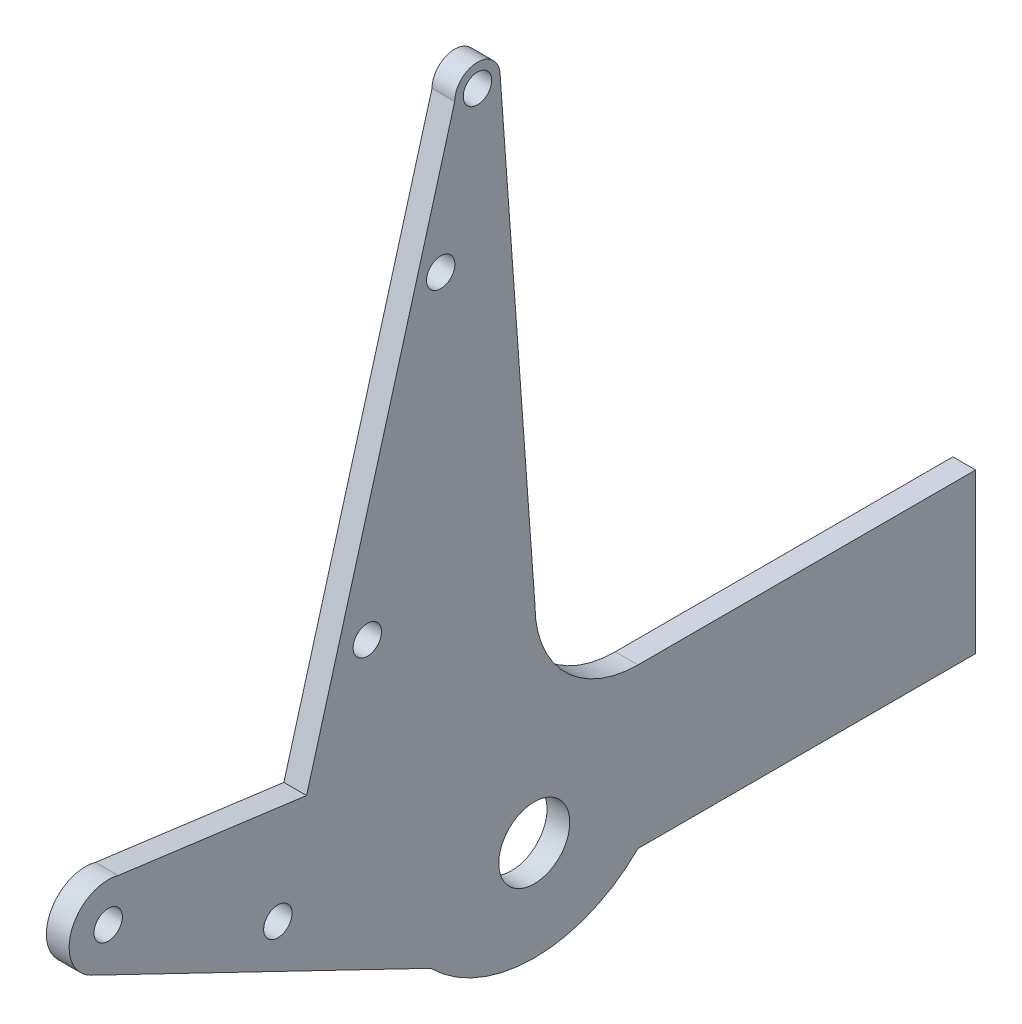
SolidWorks part; units mm, degrees
material "Hexcel AS4C (3000 Filaments)"
ref_plane "Front Plane" through (0, 0, 0) normal (0, 0, 1) x (1, 0, 0)
ref_plane "Top Plane" through (0, 0, 0) normal (0, 1, 0) x (1, 0, 0)
ref_plane "Right Plane" through (0, 0, 0) normal (1, 0, 0) x (0, 0, -1)
sketch "Sketch1" plane through (0, 0, 0) normal (1, 0, 0) x (0, 0, -1)
  line L0 (0, 0) -> (0, 18)
  line L1 (0, 0) -> (-75.75, 0)
  line L6 (0, 0) -> (0, -10)
  line L7 (0, 18) -> (-57.5, 18)
  line L8 (0, -10) -> (-57.5, -10)
  line L15 (-75.75, 0) -> (-85.75, 0)
  line L16 (-85.75, 0) -> (-85.75, 120)
  line L17 (-150.75, 0) -> (-150.75, 25)
  line L18 (-57.5, -10) -> (-75.75, -10)
  line L19 (-75.75, 0) -> (-150.75, 0)
  line L20 (-75.75, -10) -> (-94, -10)
  line L21 (-75.75, 0) -> (-75.6253, 36.1879)
  line L22 (-75.6253, 36.1879) -> (-81.75, 120)
  line L23 (-94, -10) -> (-153.7363, 18.8075)
  line L24 (-115.8226, 27.2536) -> (-150.75, 31.875)
  line L25 (-115.8226, 27.2536) -> (-89.75, 120)
  line L26 (-91.0115, -3.803) -> (-150.7478, 25.0045)
  circle A1 centre (-75.75, 0) radius 6.25
  circle A3 centre (-150.75, 25) radius 2.5
  circle A4 centre (-85.75, 120) radius 2.5
  arc A5 (-57.5, -10) -> (-94, -10) centre (-75.75, 8.25) cw
  arc A7 (-57.5, 18) -> (-75.6253, 36.1879) centre (-57.5, 36.1254) cw
  circle A8 centre (-150.75, 25) radius 6.875
  circle A9 centre (-85.75, 120) radius 4
  circle A12 centre (-120.8797, 10.6008) radius 2.5
  circle A14 centre (-92.213, 95.2087) radius 2.5
  circle A15 centre (-105.1366, 45.6356) radius 2.5
  point P25 (-161.3024, 58.3714)
  point P26 (-115.8226, 27.2536)
  point P39 (-92.213, 95.2087)
  point P40 (-105.1366, 45.6356)
  dimension "D3" = 10
  dimension "D4" = 12.5
  dimension "D8" = 5
  dimension "D11" = 5
  dimension "D16" = 13.75
  dimension "D17" = 8
  dimension "D18" = 6.88
  dimension "D19" = 5
  dimension "D21" = 5
  dimension "D22" = 5
  dimension "D1" = 18
  dimension "D2" = 75.75
  dimension "D5" = 57.5
  dimension "D6" = 25
  dimension "D7" = 75
  dimension "D9" = 120
  dimension "D10" = 10
  dimension "D12" = 57.5
  dimension "D13" = 18.25
  dimension "D14" = 18.25
  dimension "D15" = 36.1879
extrude "Boss-Extrude1" add sketch "Sketch1" along normal blind 4
sketch "Sketch2" plane through (0, 0, 0) normal (0, 0, -1) x (-1, 0, 0)
  line L1 (-4, 18) -> (0, 18)
  line L2 (-4, 18) -> (-4, -10)
  line L3 (-4, -10) -> (0, -10)
  line L4 (0, 18) -> (0, -10)
extrude "Boss-Extrude2" add sketch "Sketch2" along normal blind 1.94
